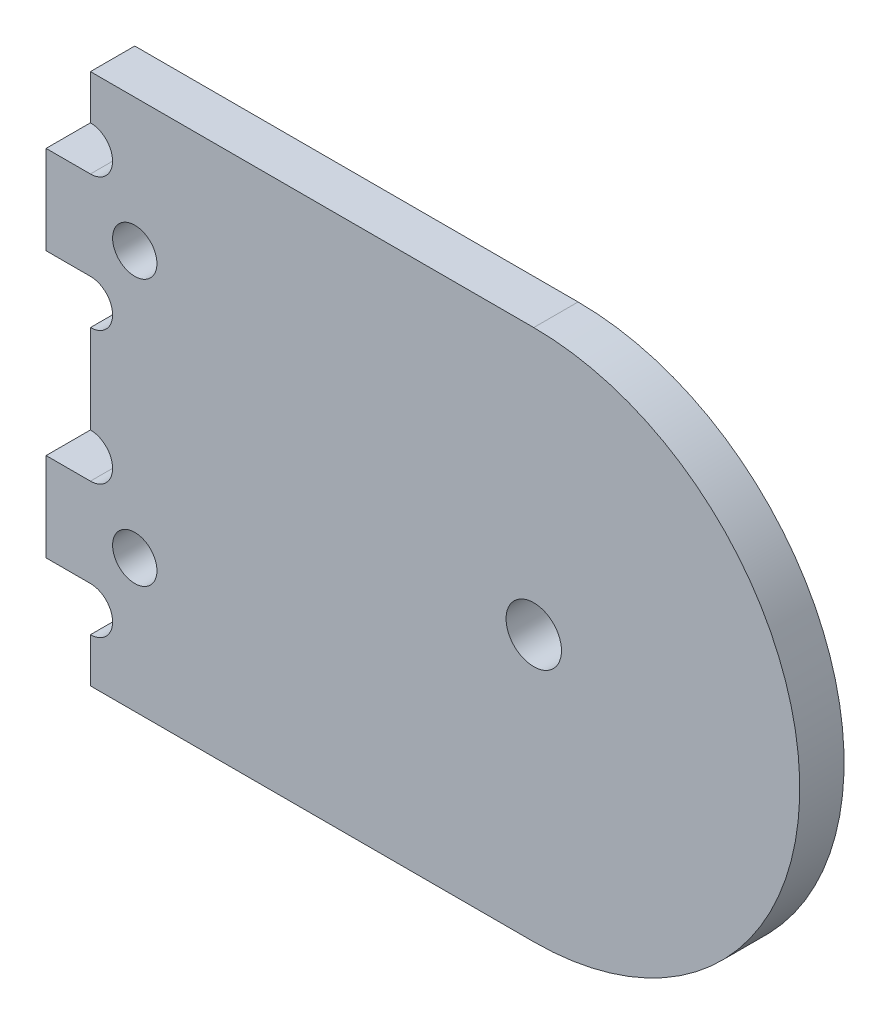
SolidWorks part; units mm, degrees
material "自訂玻璃纖維"
ref_plane "前基準面" through (0, 0, 0) normal (0, 0, 1) x (1, 0, 0)
ref_plane "上基準面" through (0, 0, 0) normal (0, 1, 0) x (1, 0, 0)
ref_plane "右基準面" through (0, 0, 0) normal (1, 0, 0) x (0, 0, -1)
sketch "草圖1" plane through (0, 0, 0) normal (0, 0, 1) x (1, 0, 0)
  line L0 (-36.0931, 13.879) -> (-16.0931, 13.879)
  line L1 (-36.0931, 13.879) -> (-36.0931, 11.879)
  line L2 (-36.0931, -10.121) -> (-16.0931, -10.121)
  line L3 (-36.0931, -2.121) -> (-38.0931, -2.121)
  line L4 (-36.0931, 9.879) -> (-38.0931, 9.879)
  line L5 (-36.0931, -6.121) -> (-38.0931, -6.121)
  line L6 (-36.0931, 5.879) -> (-38.0931, 5.879)
  line L7 (-38.0931, 9.879) -> (-38.0931, 5.879)
  line L8 (-36.0931, 3.879) -> (-36.0931, -0.121)
  line L9 (-38.0931, -2.121) -> (-38.0931, -6.121)
  line L10 (-36.0931, -8.121) -> (-36.0931, -10.121)
  arc A0 (-16.0931, -10.121) -> (-16.0931, 13.879) centre (-16.0931, 1.879) ccw
  circle A1 centre (-16.0931, 1.879) radius 1.25
  arc A2 (-36.0931, 9.879) -> (-36.0931, 11.879) centre (-36.0931, 10.879) ccw
  circle A3 centre (-34.0931, 7.879) radius 1
  arc A4 (-36.0931, 5.879) -> (-36.0931, 3.879) centre (-36.0931, 4.879) cw
  circle A5 centre (-34.0931, -4.121) radius 1
  arc A6 (-36.0931, -2.121) -> (-36.0931, -0.121) centre (-36.0931, -1.121) ccw
  arc A7 (-36.0931, -6.121) -> (-36.0931, -8.121) centre (-36.0931, -7.121) cw
  dimension "D3" = 2.5
  dimension "D4" = 4
  dimension "D5" = 12
  dimension "D8" = 2
  dimension "D9" = 4
  dimension "D10" = 2
  dimension "D11" = 2
  dimension "D1" = 24
  dimension "D2" = 20
extrude "填料-伸長1" add sketch "草圖1" along normal blind 2
